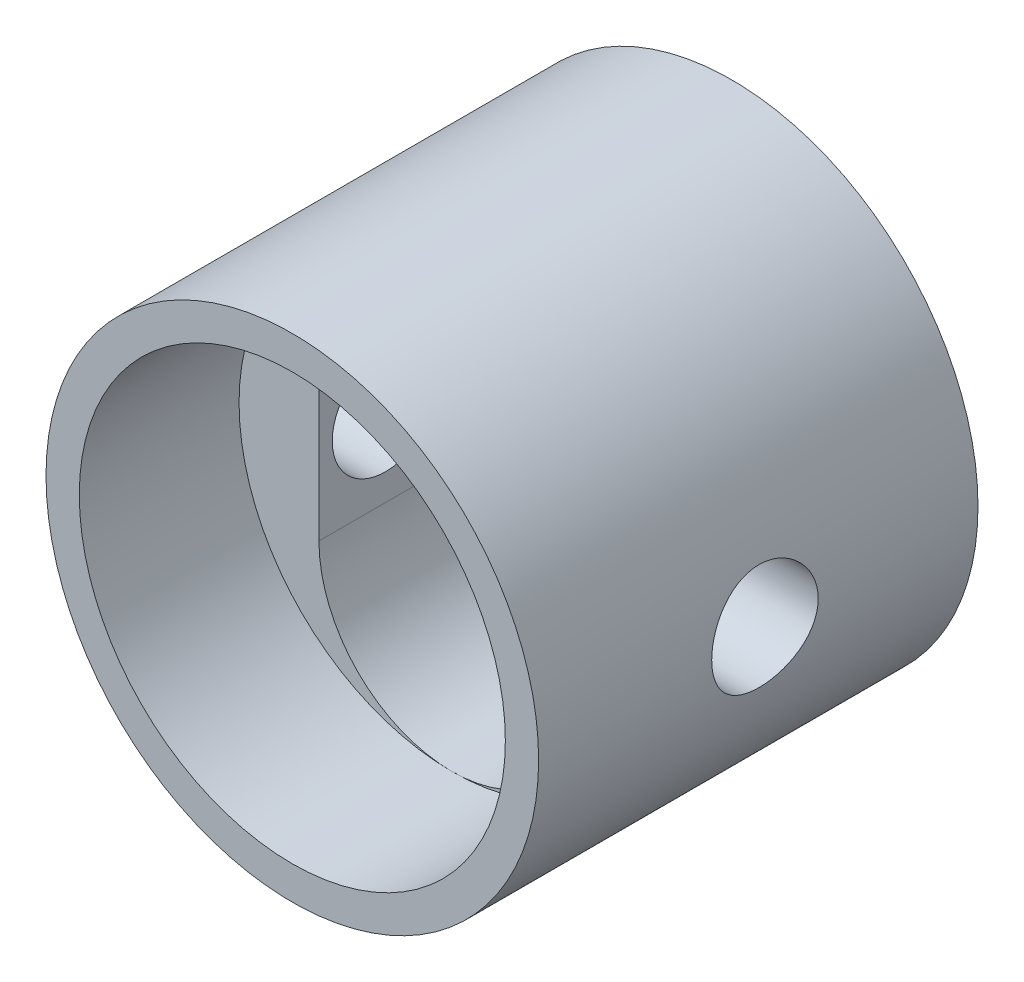
SolidWorks part; units mm, degrees
ref_plane "Plan1" through (0, 0, 0) normal (0, 0, 1) x (1, 0, 0)
ref_plane "Plan2" through (0, 0, 0) normal (0, 1, 0) x (1, 0, 0)
ref_plane "Plan3" through (0, 0, 0) normal (1, 0, 0) x (0, 0, -1)
sketch "Esquisse1" plane through (0, 0, 0) normal (0, 0, 1) x (1, 0, 0)
  circle A0 centre (0, 0) radius 9.25
  dimension "D1" = 18.5
extrude "Base-Extrusion" add sketch "Esquisse1" along normal blind 16.5
ref_plane "Plan4" through (9.25, 0, 0) normal (1, 0, 0) x (0, 0, -1)
sketch "Esquisse2" plane through (9.25, 0, 0) normal (1, 0, 0) x (0, 0, -1)
  line L0 (-16.5, 0) -> (0, 0) construction
  circle A0 centre (-8, 0) radius 2
  dimension "D1" = 4
  dimension "D2" = 8
extrude "Enlèv. mat.-Extru.1" cut sketch "Esquisse2" against normal through all
sketch "Esquisse3" plane through (0, 0, 16.5) normal (0, 0, 1) x (1, 0, 0)
  circle A0 centre (0, 0) radius 8
extrude "Enlèv. mat.-Extru.2" cut sketch "Esquisse3" against normal blind 6
sketch "Esquisse4" plane through (0, 0, 10.5) normal (0, 0, 1) x (1, 0, 0)
  line L0 (5, 3) -> (5, -3)
  line L1 (-5, 3) -> (-5, -3)
  arc A0 (5, 3) -> (-5, 3) centre (0, 3) ccw
  arc A1 (-5, -3) -> (5, -3) centre (0, -3) ccw
extrude "Enlèv. mat.-Extru.3" cut sketch "Esquisse4" against normal blind 10
